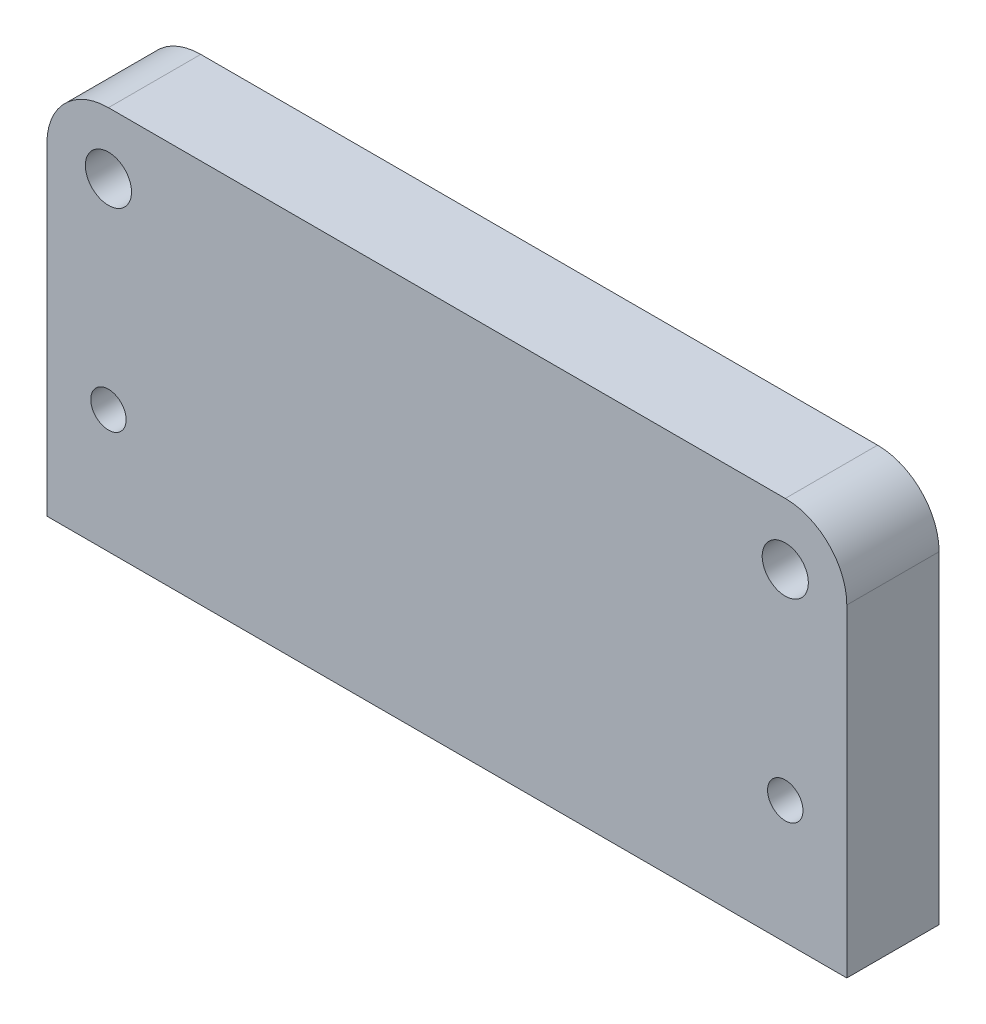
SolidWorks part; units mm, degrees
ref_plane "Front Plane" through (0, 0, 0) normal (0, 0, 1) x (1, 0, 0)
ref_plane "Top Plane" through (0, 0, 0) normal (0, 1, 0) x (1, 0, 0)
ref_plane "Right Plane" through (0, 0, 0) normal (1, 0, 0) x (0, 0, -1)
sketch "Sketch1" plane through (0, 0, 0) normal (0, 0, 1) x (1, 0, 0)
  line L0 (4, 8) -> (48, 8) construction
  line L1 (0, 0) -> (52, 0)
  line L2 (0, 0) -> (0, 21)
  line L3 (4, 21) -> (48, 21) construction
  line L4 (52, 0) -> (52, 21)
  line L5 (48, 8) -> (48, 21) construction
  line L6 (26, 8) -> (26, 15.9438) construction
  line L8 (48, 25) -> (4, 25)
  arc A0 (4, 25) -> (0, 21) centre (4, 21) ccw
  arc A1 (48, 25) -> (52, 21) centre (48, 21) cw
  circle A2 centre (4, 21) radius 1.5
  circle A3 centre (48, 21) radius 1.5
  circle A4 centre (4, 8) radius 1.15
  circle A5 centre (48, 8) radius 1.15
  dimension "D1" = 4
  dimension "D2" = 4
  dimension "D3" = 3
  dimension "D4" = 2.3
  dimension "D5" = 52
  dimension "D6" = 13
  dimension "D7" = 8
extrude "Boss-Extrude1" add sketch "Sketch1" along normal blind 6
